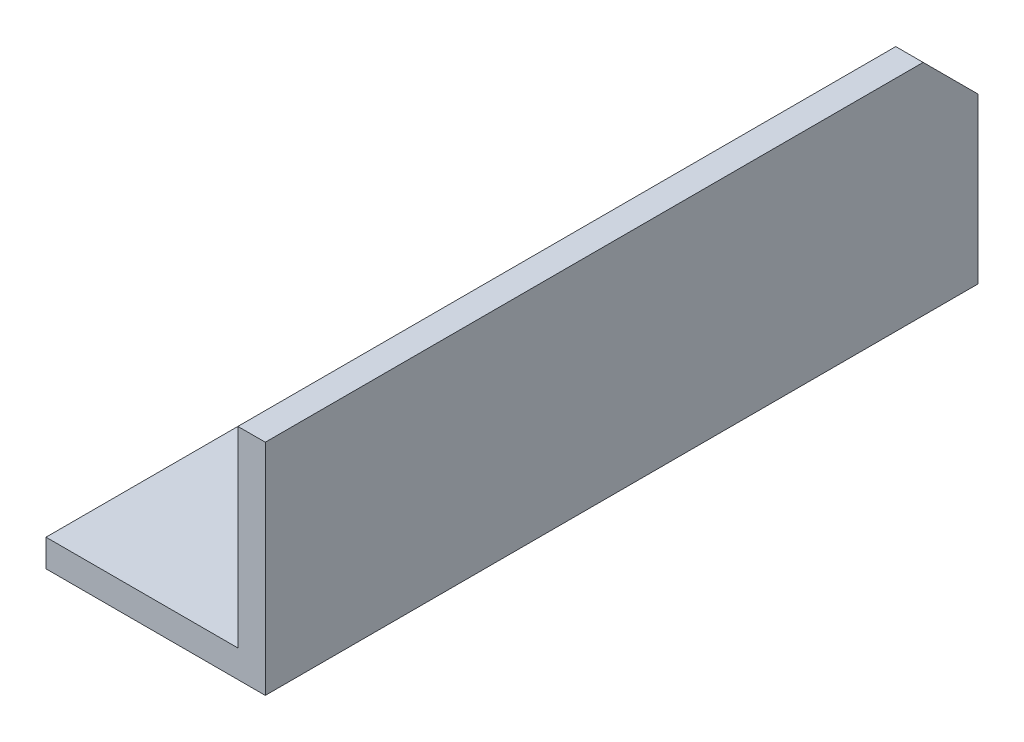
SolidWorks part; units mm, degrees
ref_plane "Front" through (0, 0, 0) normal (0, 0, 1) x (1, 0, 0)
ref_plane "Top" through (0, 0, 0) normal (0, 1, 0) x (1, 0, 0)
ref_plane "Right" through (0, 0, 0) normal (1, 0, 0) x (0, 0, -1)
sketch "Sketch2" plane through (0, 0, 0) normal (0, 0, 1) x (1, 0, 0)
  line L0 (-40, 0) -> (0, 0)
  line L1 (0, 0) -> (0, 40)
  dimension "D1" = 40
  dimension "D2" = 40
extrude "Extrude-Thin1" add sketch "Sketch2" along normal blind 65 and the other way blind 65 thin thin type one direction reverse wall 5
chamfer "Chamfer1" distance 10 angle 45 2 edges at (-40, 2.5, -65) (-2.5, 40, -65)
sketch "Sketch4" plane through (0, 5, 0) normal (0, 1, 0) x (1, 0, 0)
  line L1 (-30, 65) -> (-5, 65) construction
  line L2 (-40, 55) -> (-40, -65) construction
  circle A0 centre (-20, 38) radius 5
  dimension "D1" = 10
  dimension "D2" = 20
  dimension "D3" = 27
extrude "Cut-Extrude2" cut sketch "Sketch4" against normal blind 10
